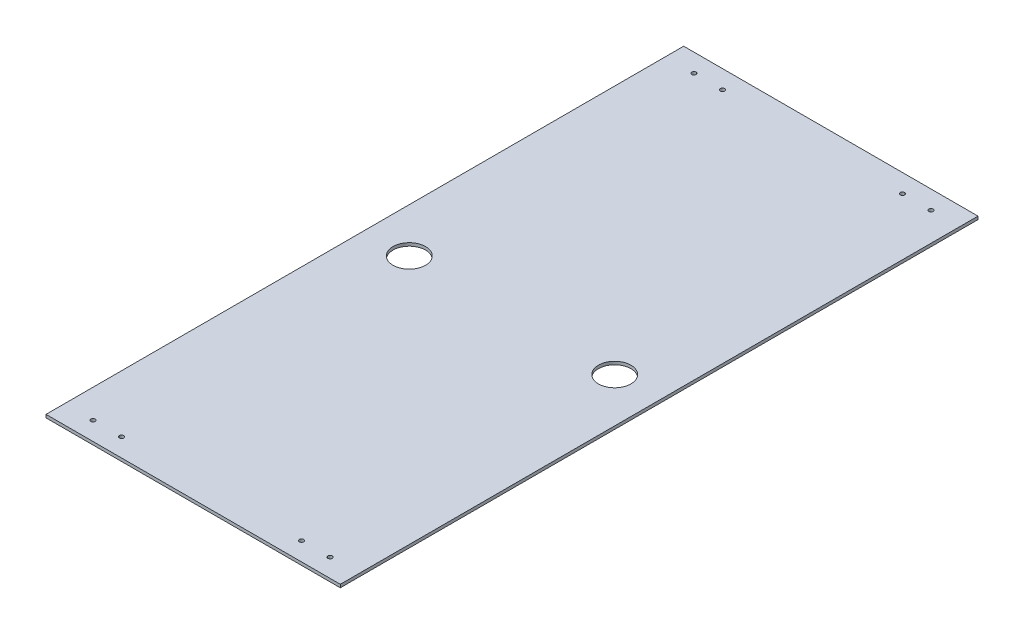
SolidWorks part; units mm, degrees
material "PC High Viscosity"
ref_plane "Front Plane" through (0, 0, 0) normal (0, 0, 1) x (1, 0, 0)
ref_plane "Top Plane" through (0, 0, 0) normal (0, 1, 0) x (1, 0, 0)
ref_plane "Right Plane" through (0, 0, 0) normal (1, 0, 0) x (0, 0, -1)
sketch "Sketch1" plane through (0, 0, 0) normal (0, 1, 0) x (1, 0, 0)
  line L0 (0, 330.2) -> (304.8, 330.2) construction
  line L1 (0, 0) -> (304.8, 0)
  line L2 (0, 0) -> (0, 660.4)
  line L3 (0, 660.4) -> (304.8, 660.4)
  line L4 (304.8, 0) -> (304.8, 660.4)
  line L5 (0, 19.05) -> (304.8, 19.05) construction
  line L6 (0, 641.35) -> (304.8, 641.35) construction
  circle A0 centre (46.0248, 330.2) radius 16.8275
  circle A1 centre (258.7752, 330.2) radius 16.8275
  circle A2 centre (29.6333, 19.05) radius 2.2479
  circle A3 centre (59.2667, 19.05) radius 2.2479
  circle A4 centre (245.5333, 19.05) radius 2.2479
  circle A5 centre (275.1667, 19.05) radius 2.2479
  circle A6 centre (275.1667, 641.35) radius 2.2479
  circle A7 centre (245.5333, 641.35) radius 2.2479
  circle A8 centre (59.2667, 641.35) radius 2.2479
  circle A9 centre (29.6333, 641.35) radius 2.2479
  dimension "D5" = 4.4958
  dimension "D16" = 33.655
  dimension "D1" = 304.8
  dimension "D2" = 660.4
  dimension "D3" = 19.05
  dimension "D4" = 19.05
  dimension "D6" = 29.6333
  dimension "D7" = 29.6333
  dimension "D8" = 29.6333
  dimension "D9" = 29.6333
  dimension "D10" = 29.6333
  dimension "D11" = 29.6333
  dimension "D12" = 29.6333
  dimension "D13" = 29.6333
  dimension "D14" = 46.0248
  dimension "D15" = 46.0248
extrude "Boss-Extrude1" add sketch "Sketch1" along normal blind 3.175
